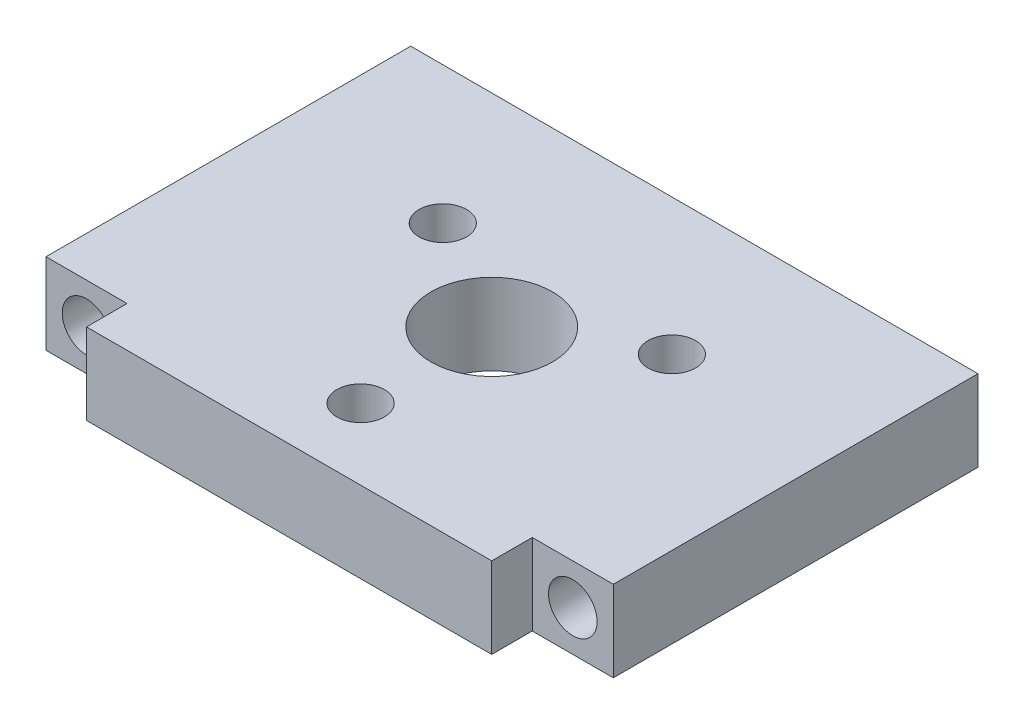
SolidWorks part; units mm, degrees
ref_plane "Plan de face" through (0, 0, 0) normal (0, 0, 1) x (1, 0, 0)
ref_plane "Plan de dessus" through (0, 0, 0) normal (0, 1, 0) x (1, 0, 0)
ref_plane "Plan de droite" through (0, 0, 0) normal (1, 0, 0) x (0, 0, -1)
sketch "Esquisse1" plane through (0, 0, 0) normal (0, 0, 1) x (1, 0, 0)
  line L1 (0, 0) -> (28, 0)
  line L2 (0, 0) -> (0, 4)
  line L3 (0, 4) -> (28, 4)
  line L4 (28, 0) -> (28, 4)
  dimension "D1" = 4
  dimension "D2" = 28
extrude "Boss.-Extru.1" add sketch "Esquisse1" along normal blind 20
sketch "Esquisse2" plane through (0, 0, 20) normal (0, 0, 1) x (1, 0, 0)
  line L0 (0, 4) -> (0, 0) construction
  line L1 (28, 4) -> (0, 4) construction
  circle A0 centre (2, 2) radius 1.2
  circle A1 centre (26, 2) radius 1.2
  point P6 (0, 2)
  dimension "D1" = 24
  dimension "D4" = 2.4
  dimension "D5" = 2.4
  dimension "D2" = 2
  dimension "D3" = 2
extrude "Enlèv. mat.-Extru.1" cut sketch "Esquisse2" against normal through all
sketch "Esquisse3" plane through (0, 4, 0) normal (0, 1, 0) x (1, 0, 0)
  line L0 (28, 0) -> (0, 0) construction
  line L1 (0, -20) -> (0, 0) construction
  circle A0 centre (14, -10) radius 3
  circle A2 centre (8.3575, -6.7731) radius 1.1736
  circle A3 centre (19.6158, -6.7269) radius 1.1736
  circle A4 centre (14.0267, -16.4999) radius 1.1736
  point P16 (14, -10)
  dimension "D1" = 6
  dimension "D4" = 6.5
  dimension "D2" = 10
  dimension "D3" = 14
  dimension "D5" = 3
extrude "Enlèv. mat.-Extru.3" cut sketch "Esquisse3" against normal through all
sketch "Esquisse4" plane through (0, 0, 20) normal (0, 0, 1) x (1, 0, 0)
  line L0 (0, 0) -> (28, 0) construction
  line L1 (0, 4) -> (4, 4)
  line L2 (0, 4) -> (0, 0)
  line L3 (0, 0) -> (4, 0)
  line L4 (4, 4) -> (4, 0)
  line L5 (28, 4) -> (0, 4) construction
  line L6 (28, 0) -> (24, 0)
  line L7 (28, 0) -> (28, 4)
  line L8 (28, 4) -> (24, 4)
  line L9 (24, 0) -> (24, 4)
  dimension "D1" = 4
  dimension "D2" = 4
extrude "Enlèv. mat.-Extru.4" cut sketch "Esquisse4" against normal blind 2
